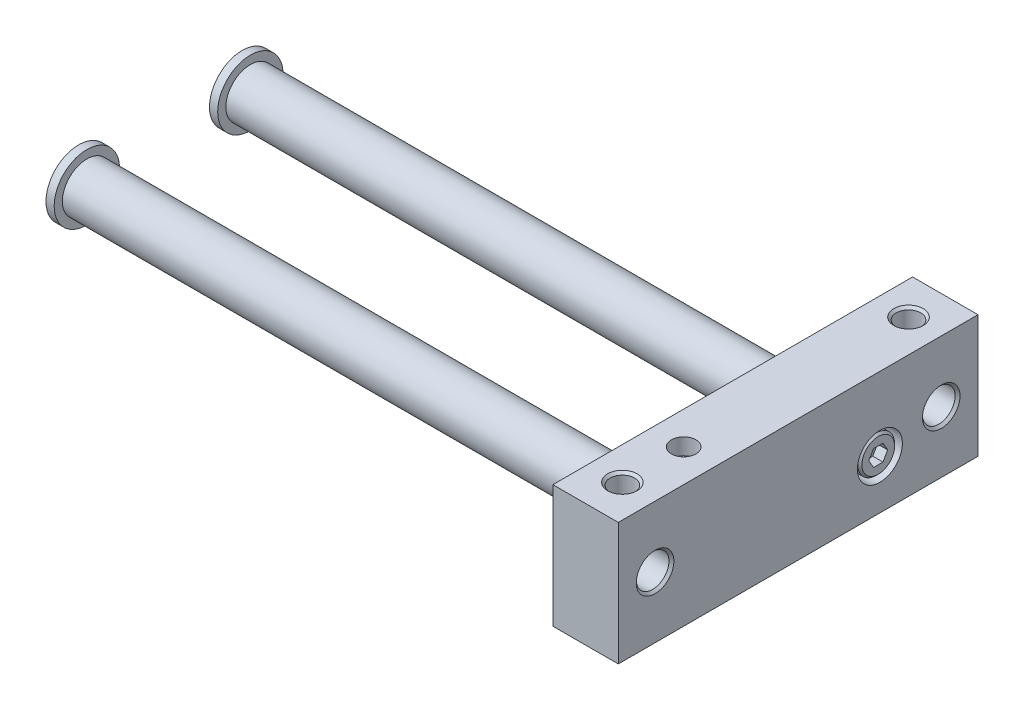
SolidWorks part; units mm, degrees
ref_plane "Plane1" through (0, 0, 0) normal (0, 0, 1) x (1, 0, 0)
ref_plane "Plane2" through (0, 0, 0) normal (0, 1, 0) x (1, 0, 0)
ref_plane "Plane3" through (0, 0, 0) normal (1, 0, 0) x (0, 0, -1)
sketch "Plate_Sketch" plane through (0, 0, 0) normal (1, 0, 0) x (0, 0, -1)
  line L0 (-22, 7.5) -> (-22, -7.5)
  line L1 (-22, -7.5) -> (22, -7.5)
  line L2 (22, -7.5) -> (22, 7.5)
  line L3 (22, 7.5) -> (-22, 7.5)
  line L4 (-24.2, 0) -> (24.2, 0) construction
  line L5 (0, -6.75) -> (0, 9.75) construction
  line L6 (0, 12.5779) -> (0, -12.5779) construction
  line L7 (16.4357, 0) -> (-16.4357, 0) construction
  dimension "C" = 44
  dimension "D" = 15
extrude "Plate" add sketch "Plate_Sketch" along normal blind 8
hole_wizard "Tapped Hole Face" positions "Tapped Hole Face Loc" profile "Tapped Hole Face Profile" tap size "M3x0.5" standard "Ansi Metric" end condition through all
sketch "Tapped Hole Face Loc" plane through (8, 0, 0) normal (1, 0, 0) x (0, 0, -1)
  line L0 (0, 0) -> (0, 21.0226) construction
  line L1 (-22, -7.5) -> (22, -7.5) construction
  point P0 (-17.5, 0)
  point P1 (17.5, 0)
  dimension "G" = 35
  dimension "E" = 7.5
sketch "Tapped Hole Face Profile" plane through (8, 0, 17.5) normal (0, 1, 0) x (0, 0, -1)
  line L0 (0, 0) -> (0, 8)
  line L1 (0, 8) -> (2, 8)
  line L2 (2, 8) -> (2, 0.3)
  line L3 (2, 0.3) -> (2.3, 0)
  line L5 (2.3, 0) -> (0, 0)
  line L6 (-2, 0.3) -> (-2.3, 0) construction
  line L11 (0, -6.35) -> (0, 107.95) construction
  dimension "Thread Major Dia." = 4
  dimension "Thru Tap Drill Depth" = 8
  dimension "Near CSink Dia." = 4.6
  dimension "Near CSink Angle" = 90
ref_plane "bottom" through (0, -8.5, 0) normal (0, -1, 0) x (1, 0, 0)
ref_plane "innerlimit" through (-9, 0, 0) normal (1, 0, 0) x (0, 0, -1)
ref_plane "strokelimit" through (-59, 0, 0) normal (1, 0, 0) x (0, 0, -1)
sketch "Rods_Sketch" plane through (-9, 0, 0) normal (-1, 0, 0) x (0, 0, 1)
  line L0 (0, -7.7893) -> (0, 7.4105) construction
  line L1 (0, -12.5779) -> (0, 12.5779) construction
  line L3 (-4, -8.5) -> (4, -8.5) construction
  circle A0 centre (-10, -1.5) radius 3
  circle A1 centre (10, -1.5) radius 3
  dimension "NN" = 6
  dimension "H" = 20
  dimension "QQ" = 7
extrude "Rods" add sketch "Rods_Sketch" along normal blind 60 and the other way up to surface (17 mm away)
sketch "Piston_Sketch" plane through (-69, 0, 0) normal (-1, 0, 0) x (0, 0, 1)
  circle A0 centre (-10, -1.5) radius 4
  circle A1 centre (10, -1.5) radius 4
  dimension "Dia" = 8
extrude "Piston" add sketch "Piston_Sketch" along normal blind 1
hole_wizard "Tapped Holes Top" positions "Tapped Holes Top Loc" profile "Tapped Holes Top Profile" tap size "M3x0.5" standard "Ansi Metric"
sketch "Tapped Holes Top Loc" plane through (0, 7.5, 0) normal (0, 1, 0) x (-1, 0, 0)
  line L0 (0, 0) -> (-11.3574, 0) construction
  line L2 (-8, -22) -> (-8, 22) construction
  line L3 (0, -17.5) -> (-7.7, -17.5) construction
  point P0 (-4, -17.5)
  point P1 (-4, 17.5)
  dimension "I" = 4
sketch "Tapped Holes Top Profile" plane through (4, 7.5, -17.5) normal (1, 0, 0) x (0, 0, 1)
  line L0 (0, 0) -> (0, 5.4204)
  line L1 (0, 5.4204) -> (1.25, 5.2)
  line L2 (1.25, 5.2) -> (1.25, 5)
  line L3 (1.25, 5) -> (1.5, 5)
  line L5 (1.5, 5) -> (1.5, 0.3)
  line L6 (1.5, 0.3) -> (1.8, 0)
  line L7 (1.8, 0) -> (0, 0)
  line L8 (-1.5, 0.3) -> (-1.8, 0) construction
  line L10 (0, 5.4204) -> (-1.25, 5.2) construction
  line L11 (0, -6.35) -> (0, 107.95) construction
  dimension "Tap Drill Dia." = 2.5
  dimension "Tap Drill Depth" = 5.2
  dimension "Thread Major Dia." = 3
  dimension "Thread Depth" = 5
  dimension "Near C'Sink Dia." = 3.6
  dimension "Near C'Sink Angle" = 90
  dimension "Drill Angle" = 160
mirror "Tapped Holes Top Mirror" about plane through (0, 0, 0) normal (0, 1, 0) of "Tapped Holes Top"
sketch "SHCS Seat_Sketch" plane through (8, 0, 0) normal (1, 0, 0) x (0, 0, -1)
  circle A0 centre (10, -1.5) radius 2.75
  circle A1 centre (10, -1.5) radius 3 construction
  dimension "Dia" = 5.5
extrude "SHCS Seat" cut sketch "SHCS Seat_Sketch" against normal blind 2.7
sketch "SHCS Head_Sketch" plane through (5.3, 0, 0) normal (1, 0, 0) x (0, 0, -1)
  circle A0 centre (10, -1.5) radius 2.25
  circle A1 centre (10, -1.5) radius 2.75 construction
  dimension "Dia" = 4.5
extrude "SHCS Head" add sketch "SHCS Head_Sketch" along normal blind 2.5
sketch "SHCS Hex_Sketch" plane through (7.8, 0, 0) normal (1, 0, 0) x (0, 0, -1)
  line L1 (10.5774, -2.5) -> (11.1547, -1.5)
  line L2 (11.1547, -1.5) -> (10.5774, -0.5)
  line L3 (10.5774, -0.5) -> (9.4226, -0.5)
  line L4 (9.4226, -0.5) -> (8.8453, -1.5)
  line L5 (8.8453, -1.5) -> (9.4226, -2.5)
  line L6 (9.4226, -2.5) -> (10.5774, -2.5)
  circle A0 centre (10, -1.5) radius 1 construction
  circle A1 centre (10, -1.5) radius 2.25 construction
  dimension "Flats" = 2
extrude "SHCS Hex" cut sketch "SHCS Hex_Sketch" against normal blind 1.25
chamfer "SHCS Cham" distance 0.25 1 edges at (7.8, -1.5, -12.25)
sketch "SS Seat_Sketch" plane through (0, 7.5, 0) normal (0, 1, 0) x (-1, 0, 0)
  line L0 (69, 10) -> (0, 10) construction
  circle A0 centre (-4, 10) radius 1.5
  dimension "Dia" = 3
extrude "SS Seat" cut sketch "SS Seat_Sketch" against normal blind 2
sketch "SS Hex_Sketch" plane through (0, 5.5, 0) normal (0, 1, 0) x (-1, 0, 0)
  line L1 (-4.75, 9.567) -> (-4, 9.134)
  line L2 (-4, 9.134) -> (-3.25, 9.567)
  line L3 (-3.25, 9.567) -> (-3.25, 10.433)
  line L4 (-3.25, 10.433) -> (-4, 10.866)
  line L5 (-4, 10.866) -> (-4.75, 10.433)
  line L6 (-4.75, 10.433) -> (-4.75, 9.567)
  circle A0 centre (-4, 10) radius 0.75 construction
  circle A1 centre (-4, 10) radius 1.5 construction
  dimension "Flats" = 1.5
extrude "SS Hex" cut sketch "SS Hex_Sketch" against normal blind 1.5
